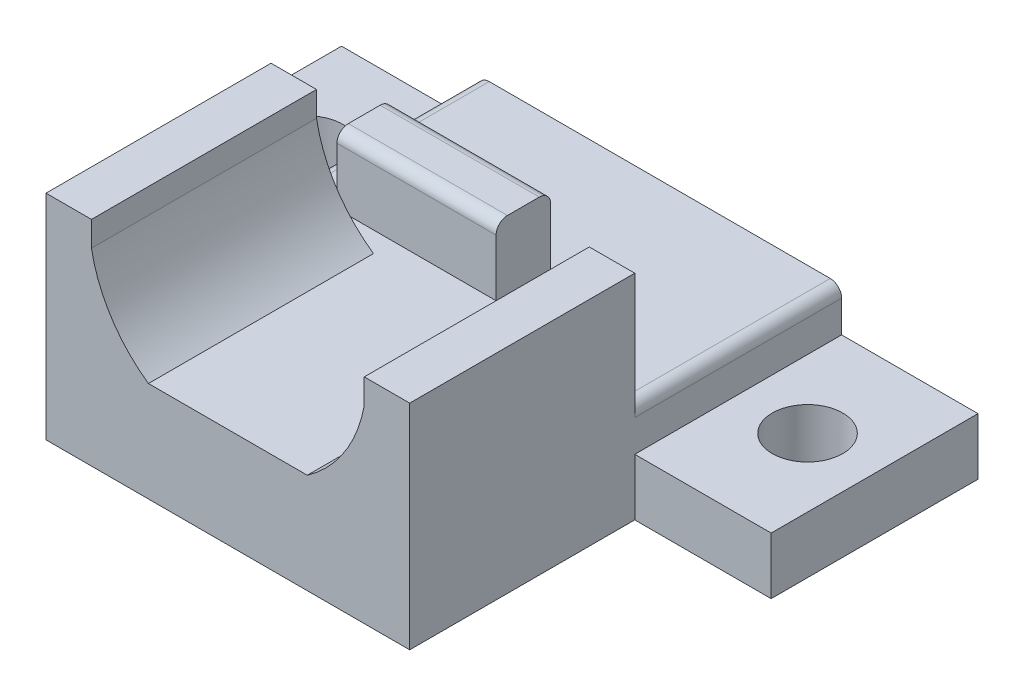
SolidWorks part; units mm, degrees
ref_plane "Front Plane" through (0, 0, 0) normal (0, 0, 1) x (1, 0, 0)
ref_plane "Top Plane" through (0, 0, 0) normal (0, 1, 0) x (1, 0, 0)
ref_plane "Right Plane" through (0, 0, 0) normal (1, 0, 0) x (0, 0, -1)
sketch "Sketch2" plane through (0, 0, 0) normal (0, 1, 0) x (1, 0, 0)
  line L1 (-8, -9.5) -> (8, -9.5)
  line L2 (-8, -9.5) -> (-8, 9.5)
  line L3 (-8, 9.5) -> (8, 9.5)
  line L4 (8, -9.5) -> (8, 9.5)
  line L5 (-8, -9.5) -> (8, 9.5) construction
  line L6 (-8, 9.5) -> (8, -9.5) construction
  point P0 (0, 0)
  dimension "D1" = 16
  dimension "D2" = 19
extrude "Boss-Extrude1" add sketch "Sketch2" along normal blind 13.3
sketch "Sketch3" plane through (0, 13.3, 0) normal (0, 1, 0) x (1, 0, 0)
  line L0 (8, 9.5) -> (-8, 9.5) construction
  line L1 (-6, -9.5) -> (6, -9.5)
  line L2 (-6, -9.5) -> (-6, 9.5)
  line L3 (-6, 9.5) -> (6, 9.5)
  line L4 (6, -9.5) -> (6, 9.5)
  line L5 (-6, -9.5) -> (6, 9.5) construction
  line L6 (-6, 9.5) -> (6, -9.5) construction
  point P0 (0, 0)
  dimension "D1" = 12
extrude "Cut-Extrude1" cut sketch "Sketch3" against normal blind 8.9
sketch "Sketch4" plane through (0, 0, 0) normal (1, 0, 0) x (0, 0, -1)
  line L0 (10.45, 0) -> (-10.45, 0) construction
  line L1 (-9.5, 13.3) -> (0.4, 13.3)
  line L2 (-9.5, 13.3) -> (-9.5, 9.4)
  line L3 (-9.5, 9.4) -> (0.4, 9.4)
  line L4 (0.4, 13.3) -> (0.4, 9.4)
  dimension "D1" = 9.9
  dimension "D2" = 9.4
extrude "Cut-Extrude2" cut sketch "Sketch4" against normal through all both and the other way through all
sketch "Sketch5" plane through (0, 0, 0) normal (1, 0, 0) x (0, 0, -1)
  line L0 (10.45, 0) -> (-10.45, 0) construction
  line L1 (-7, 2.7) -> (-3.2, 2.7)
  line L2 (-7, 2.7) -> (-7, 1)
  line L3 (-7, 1) -> (-3.2, 1)
  line L4 (-3.2, 2.7) -> (-3.2, 1)
  line L5 (-9.5, 9.4) -> (-9.5, 0) construction
  dimension "D1" = 3.8
  dimension "D2" = 1.7
  dimension "D3" = 1
  dimension "D4" = 2.5
sketch "Sketch6" plane through (0, 0, 0) normal (0, 1, 0) x (1, 0, 0)
  line L0 (6, 9.5) -> (-6, 9.5) construction
  line L1 (-14, 9.5) -> (14, 9.5)
  line L2 (0, 9.5) -> (0, 0.4)
  line L3 (-14, 0.4) -> (14, 0.4)
  line L4 (14, 9.5) -> (14, 0.4)
  line L6 (0, -7.315) -> (0, 7.315) construction
  line L7 (-14, 9.5) -> (-14, 0.4)
  dimension "D1" = 9.1
  dimension "D2" = 14
extrude "Boss-Extrude2" add sketch "Sketch6" along normal blind 2.5 contours L4 L1 L2 L3 | L1 L7 L3 L2
sketch "Sketch7" plane through (0, 2.5, 0) normal (0, 1, 0) x (1, 0, 0)
  line L0 (-8, 9.5) -> (-8, 0.4) construction
  line L1 (-14, 9.5) -> (-8, 9.5) construction
  line L2 (0, -5.17) -> (0, 5.17) construction
  line L3 (-14, 9.5) -> (-14, 0.4) construction
  circle A0 centre (-11, 5) radius 1.55
  circle A1 centre (11, 5) radius 1.55
  dimension "D1" = 3.1
  dimension "D2" = 3
  dimension "D3" = 4.5
  dimension "D4" = 3
extrude "Cut-Extrude4" cut sketch "Sketch7" against normal through all both and the other way through all
sketch "Sketch14" plane through (0, 0, 0) normal (0, 0, 1) x (1, 0, 0)
  line L1 (-6, 13.3) -> (6, 13.3)
  line L2 (-6, 13.3) -> (-6, 4.4)
  line L3 (-6, 4.4) -> (6, 4.4)
  line L4 (6, 13.3) -> (6, 4.4)
sketch "Sketch15" plane through (0, 0, 0) normal (0, 0, 1) x (1, 0, 0)
  line L0 (0, -5.17) -> (0, 5.17) construction
  line L1 (-6, 4.4) -> (6, 4.4) construction
  line L2 (-6, 4.4) -> (6, 4.4)
  line L7 (-6, 13.3) -> (6, 13.3)
  line L8 (-6, 13.3) -> (-6, 9.4)
  line L9 (-6, 9.4) -> (6, 9.4)
  line L10 (6, 13.3) -> (6, 9.4)
  line L11 (6, 13.3) -> (6, 4.4)
  line L12 (6, 13.3) -> (6, 4.4)
  line L13 (-6, 13.3) -> (-6, 4.4)
  circle A0 centre (0, 9.4) radius 6.1
  dimension "D1" = 12.2
  dimension "D2" = 5
extrude "Boss-Extrude3" add sketch "Sketch14" along normal blind 9.5 and the other way blind 9.1
extrude "Cut-Extrude9" cut sketch "Sketch15" against normal through all both and the other way through all contours L7 A0 | L9 A0 L7 | L9 A0 L2 | A0 L7 L8
fillet "Fillet4" radius 0.9 2 edges at (-6, 4.4, -9.3) (6, 4.4, -9.3)
sketch "Sketch16" plane through (0, 0, -9.5) normal (0, 0, -1) x (-1, 0, 0)
  line L0 (-5.1, 4.4) -> (5.1, 4.4) construction
  line L1 (-8.1456, 4.4) -> (8, 4.4)
  line L2 (-8.1456, 4.4) -> (-8.1456, 13.3)
  line L3 (-8.1456, 13.3) -> (8, 13.3)
  line L4 (8, 4.4) -> (8, 13.3)
  point P7 (-8.1456, 13.3)
extrude "Cut-Extrude10" cut sketch "Sketch16" against normal blind 9.1
sketch "Sketch17" plane through (0, 4.4, 0) normal (0, 1, 0) x (1, 0, 0)
  line L1 (-6, 3.7) -> (1, 3.7)
  line L2 (-6, 3.7) -> (-6, 1.3)
  line L3 (-6, 1.3) -> (1, 1.3)
  line L4 (1, 3.7) -> (1, 1.3)
  line L5 (-3.4943, 0.4) -> (-6, 0.4) construction
  line L6 (-6, 0.4) -> (-6, -9.5) construction
  dimension "D1" = 0.9
  dimension "D2" = 0
  dimension "D3" = 7
  dimension "D4" = 2.4
extrude "Boss-Extrude4" add sketch "Sketch17" along normal blind 3
fillet "Fillet6" radius 0.5 1 edges at (-2.5, 7.4, -3.7)
fillet "Fillet7" radius 0.5 1 edges at (-2.5, 7.4, -1.3)
fillet "Fillet8" radius 0.5 2 edges at (8, 4.4, -4.95) (-8, 4.4, -4.95)
